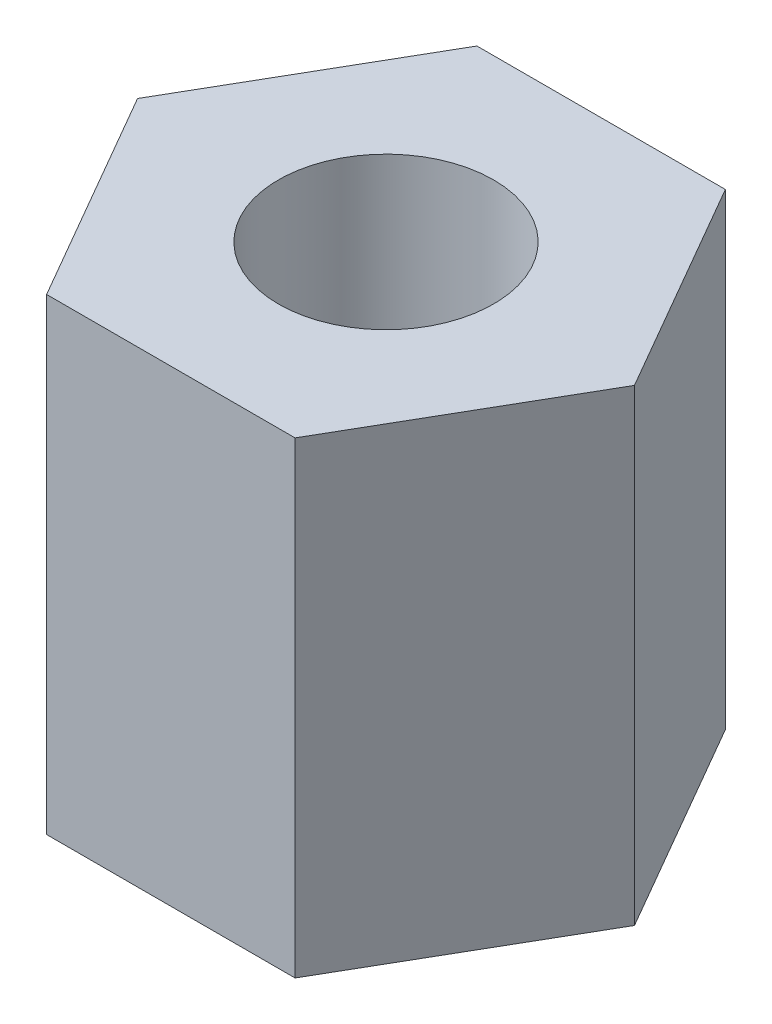
SolidWorks part; units mm, degrees
ref_plane "Front Plane" through (0, 0, 0) normal (0, 0, 1) x (1, 0, 0)
ref_plane "Top Plane" through (0, 0, 0) normal (0, 1, 0) x (1, 0, 0)
ref_plane "Right Plane" through (0, 0, 0) normal (1, 0, 0) x (0, 0, -1)
sketch "Sketch1" plane through (0, 0, 0) normal (0, 1, 0) x (1, 0, 0)
  line L1 (5.3116, 0) -> (2.6558, 4.6)
  line L2 (2.6558, 4.6) -> (-2.6558, 4.6)
  line L3 (-2.6558, 4.6) -> (-5.3116, 0)
  line L4 (-5.3116, 0) -> (-2.6558, -4.6)
  line L5 (-2.6558, -4.6) -> (2.6558, -4.6)
  line L6 (2.6558, -4.6) -> (5.3116, 0)
  circle A0 centre (0, 0) radius 4.6 construction
  circle A1 centre (0, 0) radius 2.3
  dimension "D2" = 4.6
  dimension "D1" = 9.2
extrude "Boss-Extrude1" add sketch "Sketch1" along normal mid plane 10
